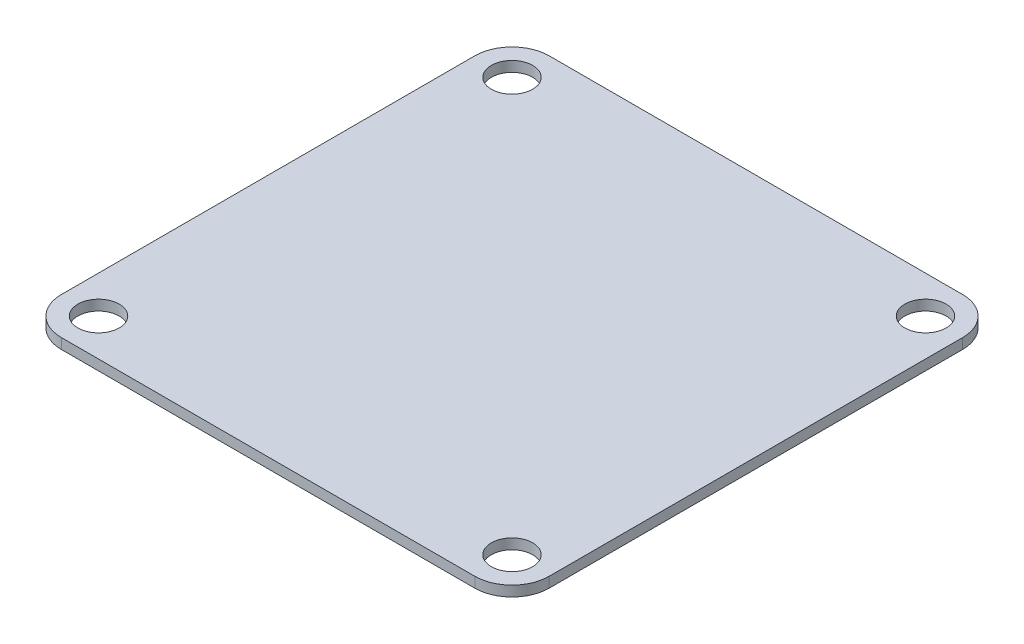
SolidWorks part; units mm, degrees
ref_plane "Front" through (0, 0, 0) normal (0, 0, 1) x (1, 0, 0)
ref_plane "Top" through (0, 0, 0) normal (0, 1, 0) x (1, 0, 0)
ref_plane "Right" through (0, 0, 0) normal (1, 0, 0) x (0, 0, -1)
sketch "草图1" plane through (0, 0, 0) normal (0, 1, 0) x (1, 0, 0)
  line L0 (-100, 118) -> (100, 118)
  line L5 (-100, 100) -> (0, 0) construction
  line L6 (-92.9289, -92.9289) -> (100, 100) construction
  line L7 (118, 100) -> (118, -100)
  line L8 (100, -118) -> (-100, -118)
  line L9 (-118, -100) -> (-118, 100)
  line L13 (87.2721, -87.2721) -> (92.9289, -92.9289) construction
  circle A0 centre (100, 100) radius 10
  circle A1 centre (100, -100) radius 10
  circle A2 centre (-100, -100) radius 10
  circle A3 centre (-100, 100) radius 10
  arc A5 (-100, 118) -> (-118, 100) centre (-100, 100) ccw
  arc A6 (118, 100) -> (100, 118) centre (100, 100) ccw
  arc A7 (100, -118) -> (118, -100) centre (100, -100) ccw
  arc A8 (-118, -100) -> (-100, -118) centre (-100, -100) ccw
  circle A9 centre (-100, 100) radius 18 construction
  point P0 (0, 0)
  point P16 (0, 0)
  point P24 (0, 0)
  point P34 (0, 0)
  dimension "D3" = 20
  dimension "D2" = 200
  dimension "D5" = 8
  dimension "D4" = 4
  dimension "D6" = 4
  dimension "D7" = 4
extrude "凸台-拉伸1" add sketch "草图1" along normal blind 5
